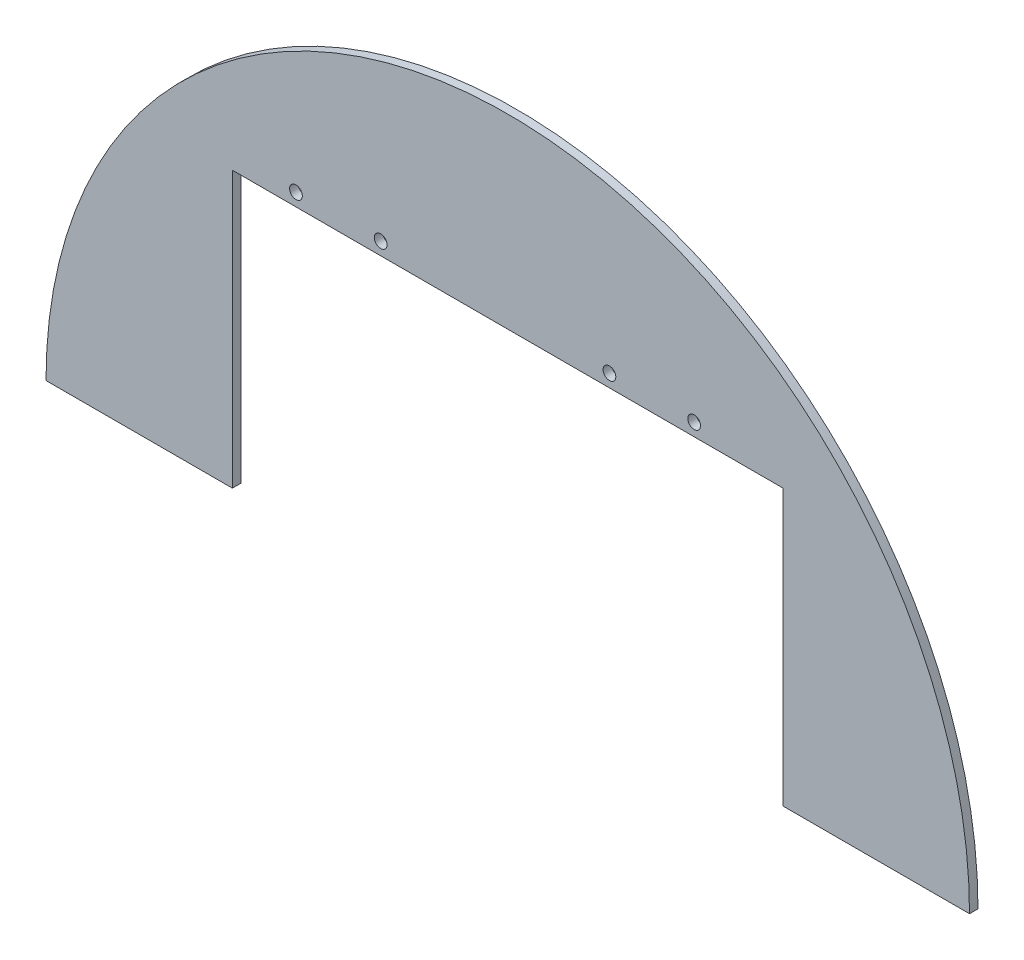
SolidWorks part; units mm, degrees
material "Thornel Mat VMA"
ref_plane "前视基准面" through (0, 0, 0) normal (0, 0, 1) x (1, 0, 0)
ref_plane "上视基准面" through (0, 0, 0) normal (0, 1, 0) x (1, 0, 0)
ref_plane "右视基准面" through (0, 0, 0) normal (1, 0, 0) x (0, 0, -1)
sketch "草图1" plane through (0, 0, 0) normal (0, 0, 1) x (1, 0, 0)
  line L0 (109, 0) -> (-109, 0)
  line L1 (-65, 65) -> (65, 65)
  line L2 (-65, 65) -> (-65, -65)
  line L3 (-65, -65) -> (65, -65)
  line L4 (65, 65) -> (65, -65)
  line L5 (-65, 65) -> (65, -65) construction
  line L6 (-65, -65) -> (65, 65) construction
  circle A0 centre (0, 0) radius 91.9239
  circle A1 centre (0, 0) radius 109
  point P0 (0, 0)
  dimension "D3" = 218
  dimension "D1" = 130
  dimension "D2" = 130
extrude "凸台-拉伸1" add sketch "草图1" along normal mid plane 2 contours L0 A1 A0 | L2 A0 L0 | L0 A0 L4 | L1 A0
sketch "草图2" plane through (0, 0, 1) normal (0, 0, 1) x (1, 0, 0)
  circle A0 centre (44, 68) radius 1.5 construction
  circle A1 centre (24, 68) radius 1.5 construction
  circle A2 centre (-30, 68) radius 1.5 construction
  circle A3 centre (-50, 68) radius 1.5 construction
  circle A4 centre (44, 68) radius 1.5
  circle A5 centre (24, 68) radius 1.5
  circle A6 centre (-30, 68) radius 1.5
  circle A7 centre (-50, 68) radius 1.5
extrude "切除-拉伸1" cut sketch "草图2" against normal blind 10
